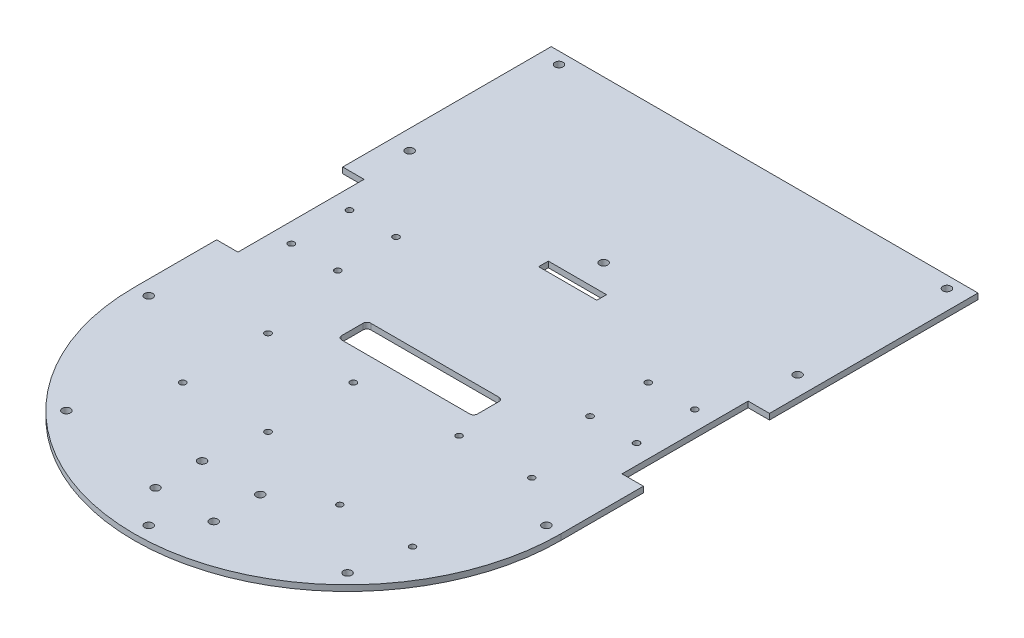
SolidWorks part; units mm, degrees
ref_plane "前视基准面" through (0, 0, 0) normal (0, 0, 1) x (1, 0, 0)
ref_plane "上视基准面" through (0, 0, 0) normal (0, 1, 0) x (1, 0, 0)
ref_plane "右视基准面" through (0, 0, 0) normal (1, 0, 0) x (0, 0, -1)
sketch "草图1" plane through (0, 0, 0) normal (0, 1, 0) x (1, 0, 0)
  line L0 (0, 0) -> (-173.2727, 0) construction
  line L2 (-110, 0) -> (-110, 140)
  line L3 (-110, 140) -> (110, 140)
  line L4 (110, 0) -> (110, 140)
  arc A0 (-110, 0) -> (110, 0) centre (0, 0) ccw
  point P0 (0, 0)
  dimension "D3" = 140
  dimension "D1" = 220
extrude "凸台-拉伸1" add sketch "草图1" along normal mid plane 3 contours L4 L3 L2 A0
sketch "草图3" plane through (0, 0, 0) normal (0, 1, 0) x (1, 0, 0)
  line L0 (0, 0) -> (0, 151.8459) construction
  line L1 (0, 0) -> (182.1542, 0) construction
  circle A0 centre (65, 90) radius 1.6
  circle A1 centre (89, 90) radius 1.6
  circle A2 centre (89, 60) radius 1.6
  circle A3 centre (65, 60) radius 1.6
  circle A4 centre (-65, 60) radius 1.6
  circle A5 centre (-89, 60) radius 1.6
  circle A6 centre (-89, 90) radius 1.6
  circle A7 centre (-65, 90) radius 1.6
  dimension "D1" = 3.2
  dimension "D4" = 30
  dimension "D5" = 24
  dimension "D7" = 65
  dimension "D8" = 90
  dimension "D2" = 2
  dimension "D3" = 2
extrude "切除-拉伸1" cut sketch "草图3" along normal through all both and the other way through all
sketch "草图4" plane through (0, 0, 0) normal (0, 1, 0) x (1, 0, 0)
  line L1 (-35, 45) -> (35, 45)
  line L2 (-35, 45) -> (-35, 30)
  line L3 (-35, 30) -> (35, 30)
  line L4 (35, 45) -> (35, 30)
  line L5 (-35, 45) -> (35, 30) construction
  line L6 (-35, 30) -> (35, 45) construction
  line L7 (-15, 118.5) -> (15, 118.5)
  line L8 (-15, 118.5) -> (-15, 113.5)
  line L9 (-15, 113.5) -> (15, 113.5)
  line L10 (15, 118.5) -> (15, 113.5)
  line L11 (-15, 118.5) -> (15, 113.5) construction
  line L12 (-15, 113.5) -> (15, 118.5) construction
  point P0 (0, 37.5)
  point P5 (0, 116)
  point P11 (0, 113.5)
  dimension "D1" = 70
  dimension "D2" = 15
  dimension "D3" = 45
  dimension "D4" = 5
  dimension "D5" = 30
  dimension "D6" = 76
extrude "切除-拉伸2" cut sketch "草图4" along normal through all both and the other way through all
sketch "草图5" plane through (0, 1.5, 0) normal (0, 1, 0) x (1, 0, 0)
  circle A0 centre (-55, -30) radius 1.6
  circle A1 centre (-11, -30) radius 1.6
  circle A2 centre (-11, 14) radius 1.6
  circle A3 centre (-55, 14) radius 1.6
  dimension "D1" = 3.2
  dimension "D7" = 44
  dimension "D2" = 30
  dimension "D3" = 55
  dimension "D6" = 44
  dimension "D4" = 2
  dimension "D5" = 2
extrude "切除-拉伸4" cut sketch "草图5" against normal through all
fillet "圆角1" radius 2 4 edges at (35, 0, -30) (35, 0, -45) (-35, 0, -30) (-35, 0, -45)
sketch "草图7" plane through (0, 1.5, 0) normal (0, 1, 0) x (1, 0, 0)
  circle A0 centre (-15, -60) radius 2.1
  circle A1 centre (15, -60) radius 2.1
  circle A2 centre (15, -84) radius 2.1
  circle A3 centre (-15, -84) radius 2.1
  dimension "D1" = 4.2
  dimension "D2" = 60
  dimension "D3" = 15
  dimension "D6" = 24
  dimension "D7" = 30
  dimension "D4" = 2
  dimension "D5" = 2
extrude "切除-拉伸5" cut sketch "草图7" against normal through all
sketch "草图8" plane through (0, 1.5, 0) normal (0, 1, 0) x (1, 0, 0)
  line L0 (-89, 90) -> (-89, 60) construction
  line L1 (-127, 42.5) -> (-99, 42.5)
  line L2 (-127, 42.5) -> (-127, 107.5)
  line L3 (-127, 107.5) -> (-99, 107.5)
  line L4 (-99, 42.5) -> (-99, 107.5)
  line L5 (-127, 42.5) -> (-99, 107.5) construction
  line L6 (-127, 107.5) -> (-99, 42.5) construction
  line L7 (0, 0) -> (0, 150.2782) construction
  line L8 (127, 107.5) -> (99, 107.5)
  line L9 (99, 42.5) -> (99, 107.5)
  line L10 (127, 42.5) -> (99, 42.5)
  line L11 (127, 42.5) -> (127, 107.5)
  line L12 (127, 42.5) -> (99, 107.5) construction
  line L13 (127, 107.5) -> (99, 42.5) construction
  point P0 (-113, 75)
  point P6 (-89, 75)
  point P7 (-99, 75)
  dimension "D1" = 28
  dimension "D2" = 65
  dimension "D3" = 10
extrude "切除-拉伸6" cut sketch "草图8" against normal through all
sketch "草图9" plane through (0, 1.5, 0) normal (0, 1, 0) x (1, 0, 0)
  circle A0 centre (0, 0) radius 102.5 construction
  circle A1 centre (0, -102.5) radius 2.1
  circle A2 centre (-72.4784, -72.4784) radius 2.1
  circle A3 centre (-102.5, 0) radius 2.1
  circle A7 centre (102.5, 0) radius 2.1
  circle A8 centre (72.4784, -72.4784) radius 2.1
  circle A9 centre (-72.4784, 72.4784) radius 2.1 [skipped]
  circle A10 centre (0, 102.5) radius 2.1 [skipped]
  circle A11 centre (72.4784, 72.4784) radius 2.1 [skipped]
  dimension "D2" = 205
  dimension "D1" = 4.2
  dimension "D3" = 8
extrude "切除-拉伸7" cut sketch "草图9" against normal through all
sketch "草图10" plane through (0, 1.5, 0) normal (0, 1, 0) x (1, 0, 0)
  line L0 (-110, 140) -> (110, 140) construction
  line L1 (-110, 107.5) -> (-110, 140) construction
  line L2 (0, 0) -> (0, 170.1543) construction
  circle A0 centre (-100, 132) radius 2.1
  circle A1 centre (100, 132) radius 2.1
  circle A2 centre (0, 132) radius 2.1
  dimension "D1" = 4.2
  dimension "D2" = 8
  dimension "D4" = 4.2
  dimension "D3" = 10
extrude "切除-拉伸8" cut sketch "草图10" against normal blind 10
sketch "草图11" plane through (0, 1.5, 0) normal (0, 1, 0) x (1, 0, 0)
  circle A0 centre (40, -44) radius 1.55
  circle A1 centre (77.5, -44) radius 1.55
  circle A2 centre (77.5, 17.5) radius 1.55
  circle A3 centre (40, 17.5) radius 1.55
  dimension "D1" = 3.1
  dimension "D4" = 44
  dimension "D5" = 40
  dimension "D6" = 61.5
  dimension "D7" = 37.5
  dimension "D2" = 2
  dimension "D3" = 2
extrude "切除-拉伸9" cut sketch "草图11" against normal through all
sketch "草图12" plane through (0, 1.5, 0) normal (0, 1, 0) x (1, 0, 0)
  line L0 (-110, 140) -> (110, 140) construction
  line L3 (-110, 215) -> (110, 215)
  line L7 (-110, 215) -> (-110, 140)
  line L8 (-110, 140) -> (110, 140)
  line L9 (110, 140) -> (110, 215)
  point P0 (0, 140)
  dimension "D1" = 75
extrude "凸台-拉伸2" add sketch "草图12" against normal blind 3
sketch "草图13" plane through (0, 1.5, 0) normal (0, 1, 0) x (1, 0, 0)
  line L0 (100, 132) -> (100, 228.7335) construction
  line L1 (110, 215) -> (-110, 215) construction
  line L2 (0, 0) -> (0, 269.4276) construction
  circle A0 centre (100, 209) radius 2.1
  circle A2 centre (-100, 209) radius 2.1
  dimension "D1" = 4.2
  dimension "D2" = 6
extrude "切除-拉伸10" cut sketch "草图13" against normal through all
